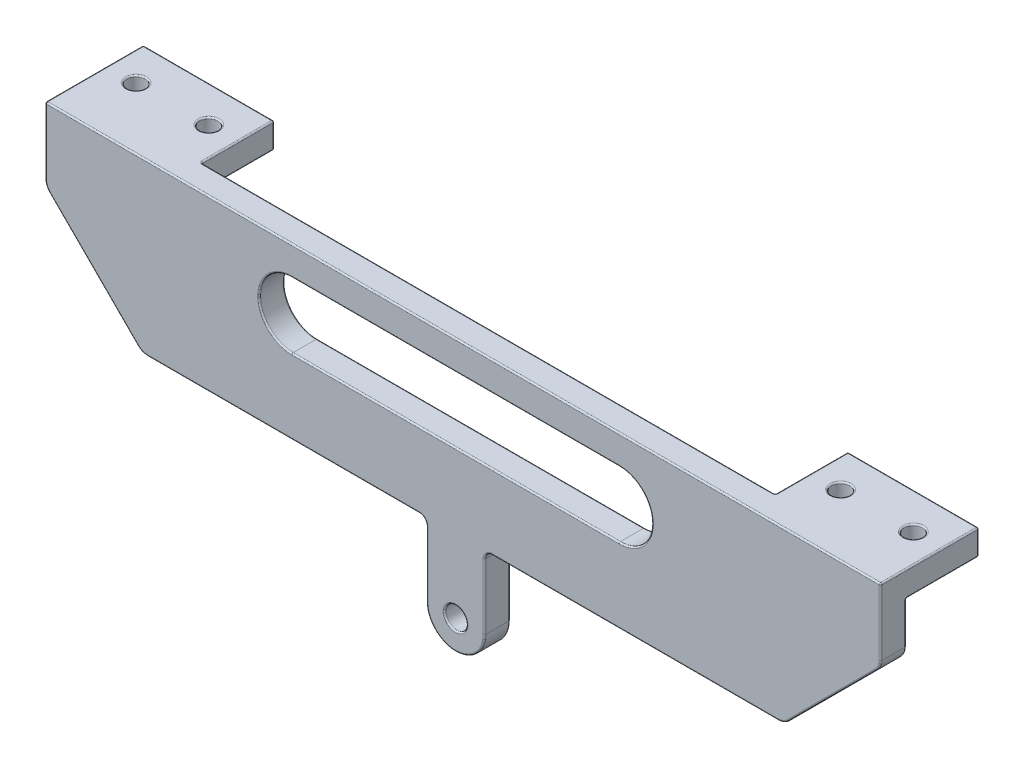
SolidWorks part; units mm, degrees
ref_plane "Front Plane" through (0, 0, 0) normal (0, 0, 1) x (1, 0, 0)
ref_plane "Top Plane" through (0, 0, 0) normal (0, 1, 0) x (1, 0, 0)
ref_plane "Right Plane" through (0, 0, 0) normal (1, 0, 0) x (0, 0, -1)
sketch "Sketch2" plane through (0, 0, 0) normal (0, 0, 1) x (1, 0, 0)
  line L0 (-2.7226, 99.9629) -> (-100, 0) construction
  line L1 (-100, 0) -> (100, 0) construction
  line L2 (100, 0) -> (-2.7226, 99.9629) construction
  line L3 (0, 0) -> (-51.3613, 49.9815) construction
  line L4 (-41.6336, 59.9778) -> (38.3664, 59.9778) construction
  line L5 (-2.7226, 99.9629) -> (-2.7226, 59.9778) construction
  circle A0 centre (-100, 0) radius 20
  circle A1 centre (0, 0) radius 20
  circle A2 centre (100, 0) radius 20
  point P2 (0, 0)
  dimension "D5" = 40
  dimension "D1" = 90
  dimension "D2" = 200
  dimension "D3" = 90
  dimension "D4" = 80
sketch "Sketch3" plane through (0, 0, 0) normal (0, 0, 1) x (1, 0, 0)
  line L0 (-57.8679, 43.2952) -> (-41.6336, 59.9778) construction
  line L1 (-2.7226, 99.9629) -> (-100, 0) construction
  line L2 (-41.6336, 59.9778) -> (38.3664, 59.9778) construction
  line L3 (38.3664, 59.9778) -> (86.3833, 13.2509) construction
  line L4 (100, 0) -> (-2.7226, 99.9629) construction
  line L5 (-50.7012, 36.3211) -> (-37.4115, 49.9778)
  line L6 (-37.4115, 49.9778) -> (34.3038, 49.9778)
  line L7 (34.3038, 49.9778) -> (79.4092, 6.0842)
  line L8 (-65.0346, 50.2694) -> (-45.8557, 69.9778)
  line L9 (-45.8557, 69.9778) -> (42.429, 69.9778)
  line L10 (42.429, 69.9778) -> (93.3574, 20.4176)
  line L11 (-65.0346, 50.2694) -> (-50.7012, 36.3211)
  line L12 (93.3574, 20.4176) -> (79.4092, 6.0842)
  line L13 (90.9165, 17.9092) -> (104.5332, 4.6583)
  line L14 (81.8501, 8.5925) -> (95.4668, -4.6583)
  line L15 (89.7741, 23.9046) -> (75.8258, 9.5713) construction
  line L16 (-2.7226, 99.9629) -> (-2.7226, 59.9778) construction
  line L17 (3.2774, 69.9778) -> (0.7302, 85.3403)
  line L18 (-8.7226, 69.9778) -> (-6.1755, 85.3403)
  circle A0 centre (100, 0) radius 3.5
  circle A1 centre (100, 0) radius 10 construction
  arc A2 (95.4668, -4.6583) -> (104.5332, 4.6583) centre (100, 0) ccw
  circle A3 centre (100, 0) radius 6.5 construction
  circle A4 centre (79.3129, 13.1546) radius 1
  circle A5 centre (86.287, 20.3213) radius 1
  circle A6 centre (-2.7226, 59.9778) radius 1.5
  circle A7 centre (-2.7226, 84.7678) radius 1.5
  arc A8 (0.7302, 85.3403) -> (-6.1755, 85.3403) centre (-2.7226, 84.7678) ccw
  circle A9 centre (-2.7226, 84.7678) radius 3.5 construction
  circle A10 centre (-51.3613, 49.9815) radius 1.5
  dimension "D4" = 20
  dimension "D5" = 7
  dimension "D12" = 2
  dimension "D13" = 2
  dimension "D14" = 3
  dimension "D19" = 3
  dimension "D3" = 27.5
  dimension "D7" = 19
  dimension "D8" = 5
  dimension "D9" = 10
  dimension "D10" = 5
  dimension "D11" = 5
  dimension "D15" = 14.79
  dimension "D17" = 6
  dimension "D18" = 6
  dimension "D1" = 10
  dimension "D2" = 10
  dimension "D6" = 3
  dimension "D16" = 2
sketch "Sketch4" plane through (0, 0, 0) normal (0, 0, 1) x (1, 0, 0)
  line L0 (-88.3212, 12.0012) -> (-51.3613, 49.9815) construction
  line L1 (-2.7226, 99.9629) -> (-100, 0) construction
  line L2 (-51.3613, 49.9815) -> (-13.6167, 13.2509) construction
  line L3 (0, 0) -> (-51.3613, 49.9815) construction
  line L4 (-79.5824, 6.6426) -> (-51.1688, 35.8406)
  line L5 (-51.1688, 35.8406) -> (-20.5908, 6.0842)
  line L6 (-93.9158, 20.5908) -> (-51.5539, 64.1223)
  line L7 (-51.5539, 64.1223) -> (-6.6426, 20.4176)
  line L8 (-95.4879, 18.9754) -> (-51.5539, 64.1223) construction
  line L9 (-81.1545, 5.0271) -> (-51.1688, 35.8406) construction
  line L10 (-93.9158, 20.5908) -> (-79.5824, 6.6426)
  line L11 (-6.6426, 20.4176) -> (-20.5908, 6.0842)
  line L12 (-91.4075, 18.1499) -> (-104.6583, 4.5332)
  line L13 (-82.0908, 9.0835) -> (-95.3417, -4.5332)
  line L14 (-9.0835, 17.9092) -> (4.5332, 4.6583)
  line L15 (-18.1499, 8.5925) -> (-4.5332, -4.6583)
  line L16 (-90.4287, 24.1742) -> (-76.0954, 10.2259) construction
  line L17 (-10.2259, 23.9046) -> (-24.1742, 9.5713) construction
  circle A0 centre (-100, 0) radius 10 construction
  circle A1 centre (0, 0) radius 3.5
  circle A2 centre (0, 0) radius 10 construction
  circle A3 centre (-100, 0) radius 3.5
  arc A4 (-104.6583, 4.5332) -> (-95.3417, -4.5332) centre (-100, 0) ccw
  arc A5 (-4.5332, -4.6583) -> (4.5332, 4.6583) centre (0, 0) ccw
  circle A6 centre (-100, 0) radius 6.5 construction
  circle A7 centre (0, 0) radius 6.5 construction
  circle A8 centre (-86.8454, 20.6871) radius 1
  circle A9 centre (-79.6787, 13.713) radius 1
  circle A10 centre (-20.6871, 13.1546) radius 1
  circle A11 centre (-13.713, 20.3213) radius 1
  dimension "D1" = 20
  dimension "D2" = 7
  dimension "D3" = 7
  dimension "D9" = 5
  dimension "D13" = 2
  dimension "D7" = 19
  dimension "D8" = 19
  dimension "D10" = 5
  dimension "D11" = 5
  dimension "D12" = 5
  dimension "D14" = 5
  dimension "D15" = 5
  dimension "D4" = 3
  dimension "D5" = 10
  dimension "D6" = 10
sketch "Sketch5" plane through (0, 0, 0) normal (0, 0, 1) x (1, 0, 0)
  line L1 (-6.7226, 69.9778) -> (-45.8557, 69.9778)
  line L3 (-59.1493, 83.2714) -> (-59.1493, 93.2714)
  line L5 (55.7226, 83.2714) -> (42.429, 69.9778)
  line L6 (42.429, 69.9778) -> (1.2774, 69.9778)
  line L7 (-45.8557, 69.9778) -> (-59.1493, 83.2714)
  line L8 (55.7226, 83.2714) -> (55.7226, 93.2714)
  line L9 (-59.1493, 93.2714) -> (55.7226, 93.2714)
  line L10 (-6.7226, 59.9778) -> (-6.7226, 69.9778)
  line L11 (1.2774, 59.9778) -> (1.2774, 69.9778)
  line L12 (-25.2226, 84.7714) -> (19.7774, 84.7714) construction
  line L13 (-25.2226, 89.2714) -> (19.7774, 89.2714)
  line L14 (-25.2226, 80.2714) -> (19.7774, 80.2714)
  circle A0 centre (-2.7226, 59.9778) radius 1.5 construction
  circle A1 centre (-2.7226, 59.9778) radius 1.5
  arc A2 (-6.7226, 59.9778) -> (1.2774, 59.9778) centre (-2.7226, 59.9778) ccw
  arc A3 (-25.2226, 89.2714) -> (-25.2226, 80.2714) centre (-25.2226, 84.7714) ccw
  arc A4 (19.7774, 80.2714) -> (19.7774, 89.2714) centre (19.7774, 84.7714) ccw
  circle A5 centre (-2.7226, 59.9778) radius 4 construction
  point P4 (-2.7226, 99.9629)
  point P22 (-2.7226, 84.7714)
  dimension "D1" = 4
  dimension "D3" = 18.8
  dimension "D4" = 18.8
  dimension "D5" = 10
  dimension "D6" = 10
  dimension "D8" = 45
  dimension "D9" = 9
  dimension "D7" = 2.5
extrude "Boss-Extrude1" add sketch "Sketch5" along normal blind 3.5
sketch "Sketch6" plane through (0, 93.2714, 0) normal (0, 1, 0) x (1, 0, 0)
  line L0 (-59.1493, 0) -> (-59.1493, 10)
  line L1 (-59.1493, 10) -> (-41.1493, 10)
  line L2 (-41.1493, 10) -> (-41.1493, 0)
  line L3 (55.7226, 0) -> (-59.1493, 0) construction
  line L4 (-41.1493, 0) -> (-59.1493, 0)
  line L5 (-1.7133, 0) -> (-1.7133, 26.3812)
  line L6 (37.7226, 0) -> (55.7226, 0)
  line L7 (37.7226, 10) -> (37.7226, 0)
  line L8 (55.7226, 10) -> (37.7226, 10)
  line L9 (55.7226, 0) -> (55.7226, 10)
  circle A2 centre (-55.1493, 5) radius 1.25
  circle A3 centre (-45.1493, 5) radius 1.25
  circle A4 centre (41.7226, 5) radius 1.25
  circle A5 centre (51.7226, 5) radius 1.25
  dimension "D3" = 2.5
  dimension "D4" = 2.5
  dimension "D6" = 4
  dimension "D5" = 4
  dimension "D1" = 18
  dimension "D2" = 10
  dimension "D7" = 10
extrude "Boss-Extrude2" add sketch "Sketch6" against normal blind 3.5 contours L4 L0 L1 L2 | L6 L9 L8 L7 | A5 | A4 | A3 | A2
fillet "Fillet1" radius 2 4 edges at (42.429, 69.9778, 1.75) (55.7226, 83.2714, 1.75) (-45.8557, 69.9778, 1.75) (-59.1493, 83.2714, 1.75)
fillet "Fillet2" radius 1 2 edges at (-6.7226, 69.9778, 1.75) (1.2774, 69.9778, 1.75)
fillet "Fillet3" radius 0.2 70 edges at (37.7226, 91.5214, -10) (55.7226, 91.5214, -10) (37.7226, 91.5214, 0) (46.7226, 89.7714, -10) (55.7226, 89.7714, -5) (46.7226, 89.7714, 0) (37.7226, 89.7714, -5) (46.7226, 93.2714, -10) (37.7226, 93.2714, -5) (52.9726, 89.7714, -5) (52.9726, 93.2714, -5) (42.9726, 89.7714, -5) (42.9726, 93.2714, -5) (-56.3993, 93.2714, -5) (-56.3993, 89.7714, -5) (-46.3993, 93.2714, -5) (-46.3993, 89.7714, -5) (-41.1493, 93.2714, -5) (-50.1493, 93.2714, -10) (-41.1493, 89.7714, -5) (-50.1493, 89.7714, 0) (-59.1493, 89.7714, -5) (-50.1493, 89.7714, -10) (-41.1493, 91.5214, -10) (-59.1493, 91.5214, -10) (-41.1493, 91.5214, 0) (-29.7226, 84.7714, 0) (-2.7226, 80.2714, 0) (24.2774, 84.7714, 0) (-29.7226, 84.7714, 3.5) (-2.7226, 80.2714, 3.5) (24.2774, 84.7714, 3.5) (-2.7226, 89.2714, 3.5) (-1.2226, 59.9778, 0) (-1.2226, 59.9778, 3.5) (-1.7133, 93.2714, 0) (-59.1493, 86.9356, 0) (-52.5025, 76.6246, 0) (-26.375, 69.9778, 0) (-6.7226, 64.4778, 0) (-2.7226, 55.9778, 0) (1.2774, 64.4778, 0) (21.939, 69.9778, 0) (49.0758, 76.6246, 0) (55.7226, 86.9356, 0) (-1.7133, 93.2714, 3.5) (-59.1493, 88.6856, 3.5) (-52.5025, 76.6246, 3.5) (-26.375, 69.9778, 3.5) (-6.7226, 64.4778, 3.5) (-2.7226, 55.9778, 3.5) (1.2774, 64.4778, 3.5) (21.939, 69.9778, 3.5) (49.0758, 76.6246, 3.5) (55.7226, 88.6856, 3.5) (55.7226, 93.2714, -3.25) (-59.1493, 93.2714, -3.25) (-58.9971, 83.3344, 0) (-45.7926, 70.13, 0) (55.5704, 83.3344, 0) (42.366, 70.13, 0) (-58.9971, 83.3344, 3.5) (-45.7926, 70.13, 3.5) (55.5704, 83.3344, 3.5) (42.366, 70.13, 3.5) (-7.0155, 69.6849, 0) (-7.0155, 69.6849, 3.5) (1.5703, 69.6849, 0) (1.5703, 69.6849, 3.5) (-2.7226, 89.2714, 0)
